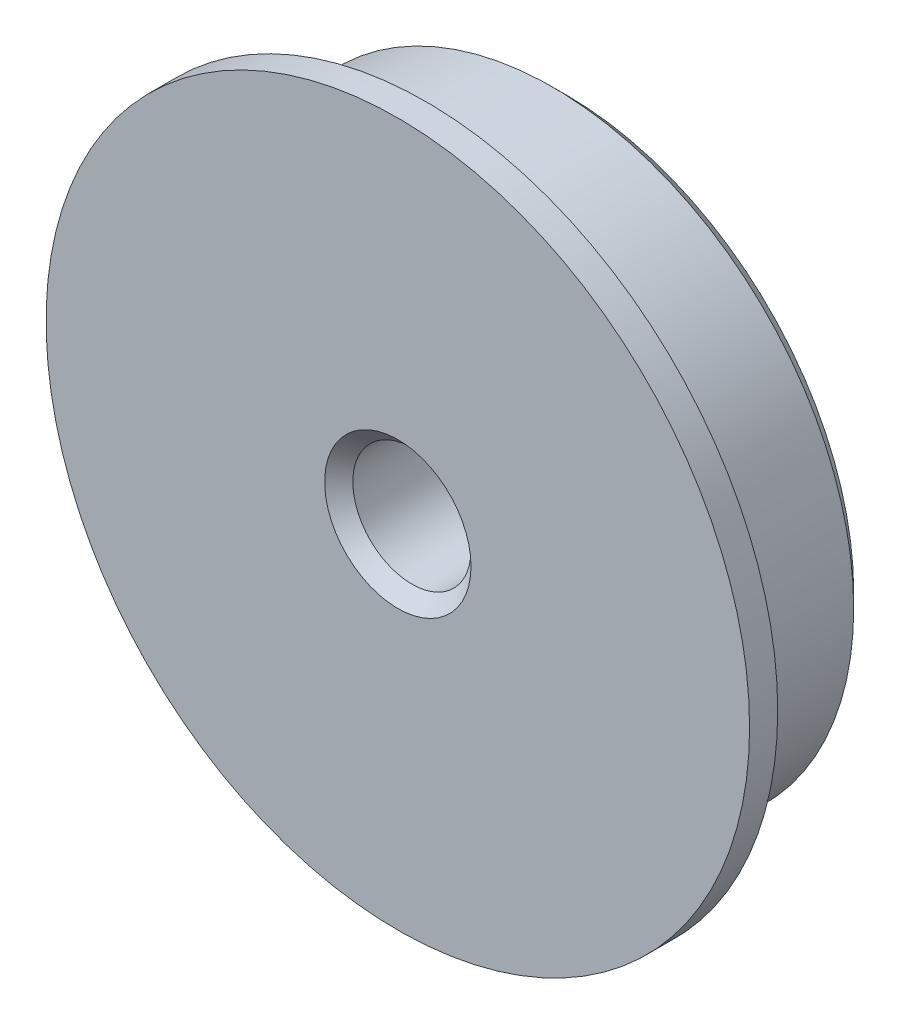
SolidWorks part; units mm, degrees
ref_plane "Plan de face" through (0, 0, 0) normal (0, 0, 1) x (1, 0, 0)
ref_plane "Plan de dessus" through (0, 0, 0) normal (0, 1, 0) x (1, 0, 0)
ref_plane "Plan de droite" through (0, 0, 0) normal (1, 0, 0) x (0, 0, -1)
sketch "Esquisse1" plane through (0, 0, 0) normal (0, 0, 1) x (1, 0, 0)
  circle A0 centre (0, 0) radius 21.4
  dimension "D1" = 42.8
extrude "Boss.-Extru.1" add sketch "Esquisse1" along normal blind 10
sketch "Esquisse2" plane through (0, 0, 10) normal (0, 0, 1) x (1, 0, 0)
  circle A0 centre (0, 0) radius 25
  dimension "D1" = 50
extrude "Boss.-Extru.2" add sketch "Esquisse2" along normal blind 2
sketch "Esquisse3" plane through (0, 0, 12) normal (0, 0, 1) x (1, 0, 0)
  circle A0 centre (0, 0) radius 4.2
  dimension "D1" = 8.4
extrude "Enlèv. mat.-Extru.1" cut sketch "Esquisse3" against normal through all both and the other way through all
chamfer "Chanfrein1" distance 1 angle 45 3 edges at (21.4, 0, 0) (4.2, 0, 0) (4.2, 0, 12)
